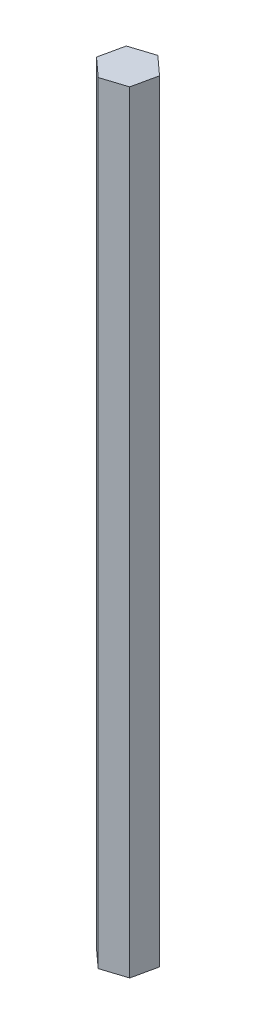
SolidWorks part; units mm, degrees
ref_plane "Front Plane" through (0, 0, 0) normal (0, 0, 1) x (1, 0, 0)
ref_plane "Top Plane" through (0, 0, 0) normal (0, 1, 0) x (1, 0, 0)
ref_plane "Right Plane" through (0, 0, 0) normal (1, 0, 0) x (0, 0, -1)
sketch "Sketch2" plane through (0, 0, 0) normal (0, 1, 0) x (1, 0, 0)
  line L1 (2.1373, -1.9404) -> (2.7491, 0.8807)
  line L2 (2.7491, 0.8807) -> (0.6118, 2.8212)
  line L3 (0.6118, 2.8212) -> (-2.1373, 1.9404)
  line L4 (-2.1373, 1.9404) -> (-2.7491, -0.8807)
  line L5 (-2.7491, -0.8807) -> (-0.6118, -2.8212)
  line L6 (-0.6118, -2.8212) -> (2.1373, -1.9404)
  circle A0 centre (0, 0) radius 2.5 construction
extrude "Boss-Extrude1" add sketch "Sketch2" along normal blind 127
sketch "Sketch3" plane through (0, 0, 0) normal (0, -1, 0) x (1, 0, 0)
  line L1 (-13.2192, 9.8568) -> (6.9753, 9.8568)
  line L2 (-13.2192, 9.8568) -> (-13.2192, -8.314)
  line L3 (-13.2192, -8.314) -> (6.9753, -8.314)
  line L4 (6.9753, 9.8568) -> (6.9753, -8.314)
extrude "Cut-Extrude1" cut sketch "Sketch3" against normal blind 38.1
